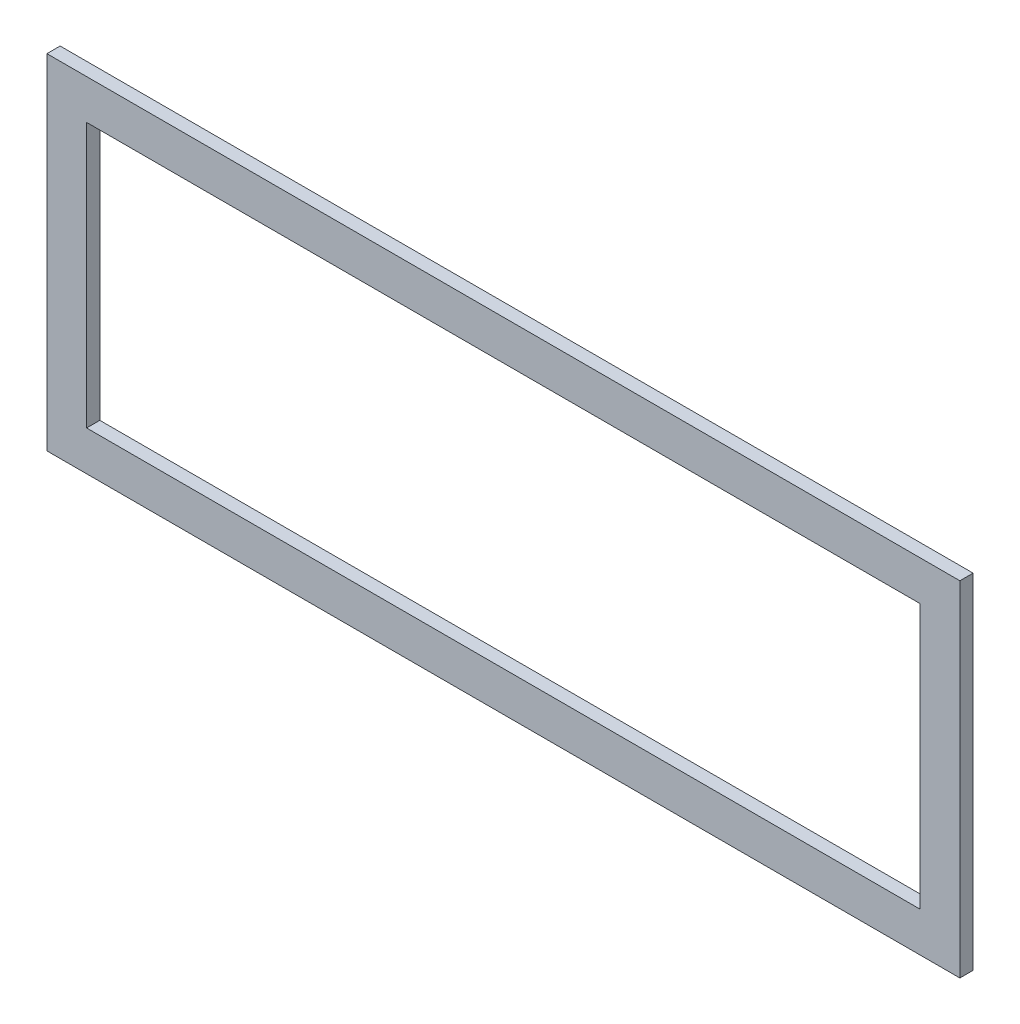
SolidWorks part; units mm, degrees
ref_plane "Front Plane" through (0, 0, 0) normal (0, 0, 1) x (1, 0, 0)
ref_plane "Top Plane" through (0, 0, 0) normal (0, 1, 0) x (1, 0, 0)
ref_plane "Right Plane" through (0, 0, 0) normal (1, 0, 0) x (0, 0, -1)
sketch "Sketch1" plane through (0, 0, 0) normal (0, 0, 1) x (1, 0, 0)
  line L1 (0, 0) -> (138, 0)
  line L2 (0, 0) -> (0, 52)
  line L3 (0, 52) -> (138, 52)
  line L4 (138, 0) -> (138, 52)
  line L6 (6, 6) -> (132, 6)
  line L7 (6, 6) -> (6, 46)
  line L8 (6, 46) -> (132, 46)
  line L9 (132, 6) -> (132, 46)
  dimension "D1" = 6
  dimension "D2" = 132
  dimension "D3" = 138
  dimension "D4" = 6
  dimension "D5" = 46
  dimension "D6" = 52
extrude "Profile" add sketch "Sketch1" along normal blind 2
equation "\"Profile_Depth\"= 2mm"
equation "\"D1@Profile\" = \"Profile_Depth\""
equation "\"Profile_Sketch_1\"= 6mm"
equation "\"D1@Sketch1\" = \"Profile_Sketch_1\""
equation "\"Profile_Sketch_2\"= 132mm"
equation "\"D2@Sketch1\" = \"Profile_Sketch_2\""
equation "\"Profile_Sketch_3\"= 138mm"
equation "\"D3@Sketch1\" = \"Profile_Sketch_3\""
equation "\"Profile_Sketch_4\"= 6mm"
equation "\"D4@Sketch1\" = \"Profile_Sketch_4\""
equation "\"Profile_Sketch_5\"= 46mm"
equation "\"D5@Sketch1\" = \"Profile_Sketch_5\""
equation "\"Profile_Sketch_6\"= 52mm"
equation "\"D6@Sketch1\" = \"Profile_Sketch_6\""
equation "\"EnvelopeWidth\"= 138mm"
equation "\"EnvelopeHeight\"= 52mm"
